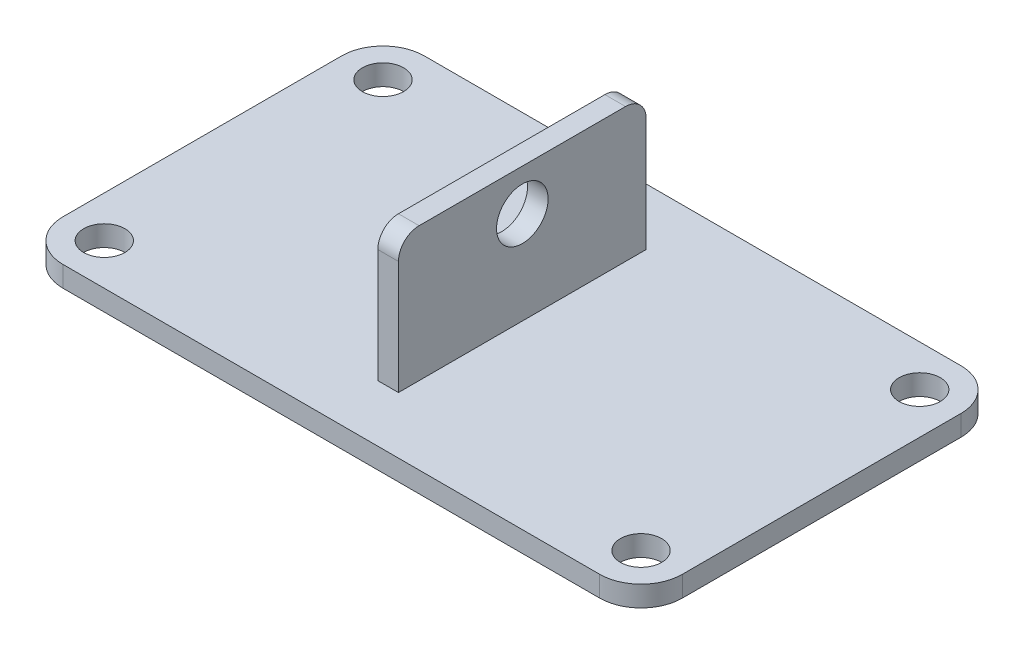
SolidWorks part; units mm, degrees
ref_plane "Front Plane" through (0, 0, 0) normal (0, 0, 1) x (1, 0, 0)
ref_plane "Top Plane" through (0, 0, 0) normal (0, 1, 0) x (1, 0, 0)
ref_plane "Right Plane" through (0, 0, 0) normal (1, 0, 0) x (0, 0, -1)
sketch "Sketch1" plane through (0, 0, 0) normal (0, 1, 0) x (1, 0, 0)
  line L1 (150, -87.5) -> (-150, -87.5)
  line L2 (150, -87.5) -> (150, 87.5)
  line L3 (150, 87.5) -> (-150, 87.5)
  line L4 (-150, -87.5) -> (-150, 87.5)
  line L5 (150, -87.5) -> (-150, 87.5) construction
  line L6 (150, 87.5) -> (-150, -87.5) construction
  point P0 (0, 0)
  dimension "D1" = 300
  dimension "D2" = 175
extrude "Boss-Extrude1" add sketch "Sketch1" along normal blind 10
sketch "Sketch2" plane through (0, 0, 0) normal (1, 0, 0) x (0, 0, -1)
  line L0 (-87.5, 10) -> (87.5, 10) construction
  line L1 (-60, 10) -> (60, 10)
  line L2 (-60, 10) -> (-60, 75)
  line L3 (-60, 75) -> (60, 75)
  line L4 (60, 10) -> (60, 75)
  line L5 (-87.5, 0) -> (87.5, 0) construction
  circle A0 centre (0, 55) radius 12.5
  point P6 (0, 10)
  point P12 (0, 0)
  dimension "D3" = 55
  dimension "D4" = 25
  dimension "D1" = 120
  dimension "D2" = 75
extrude "Boss-Extrude2" add sketch "Sketch2" along normal mid plane 10
fillet "Fillet1" radius 20 4 edges at (150, 5, -87.5) (150, 5, 87.5) (-150, 5, -87.5) (-150, 5, 87.5)
fillet "Fillet2" radius 10 2 edges at (0, 75, -60) (0, 75, 60)
hole_wizard "Hole1" positions "Sketch5" profile "Sketch6" legacy end condition through all
sketch "Sketch5" plane through (0, 10, 0) normal (0, 1, 0) x (1, 0, 0)
  point P0 (-130, -67.5)
  point P3 (-130, 67.5)
sketch "Sketch6" plane through (-130, 10, 67.5) normal (1, 0, 0) x (0, 0, 1)
  line L0 (0, 0) -> (0, 10)
  line L1 (0, 10) -> (10, 10)
  line L2 (10, 10) -> (10, 0)
  line L3 (10, 0) -> (0, 0)
  line L4 (0, 110) -> (0, -10) construction
  dimension "Diameter" = 20
  dimension "Depth" = 10
mirror "Mirror1" about plane through (0, 0, 0) normal (1, 0, 0) of "Hole1"
